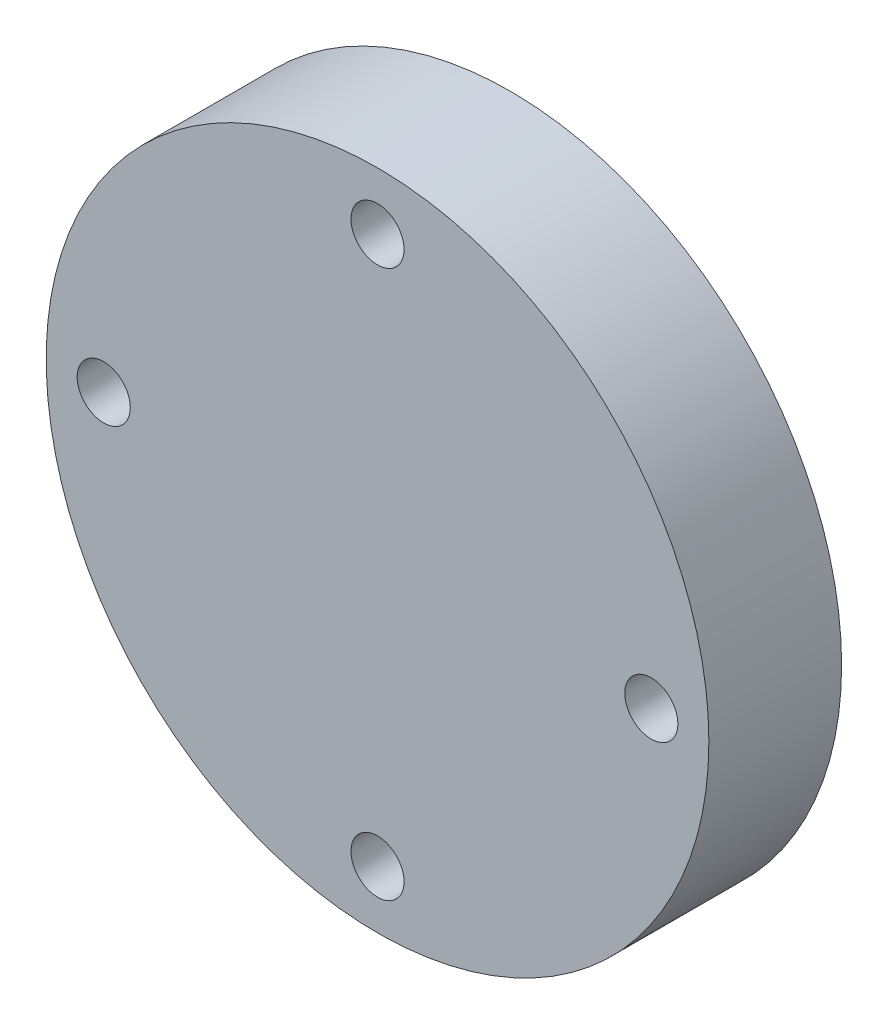
SolidWorks part; units mm, degrees
ref_plane "Front Plane" through (0, 0, 0) normal (0, 0, 1) x (1, 0, 0)
ref_plane "Top Plane" through (0, 0, 0) normal (0, 1, 0) x (1, 0, 0)
ref_plane "Right Plane" through (0, 0, 0) normal (1, 0, 0) x (0, 0, -1)
sketch "Sketch2" plane through (0, 0, 0) normal (0, 0, 1) x (1, 0, 0)
  circle A0 centre (0, 0) radius 19.9686
  circle A5 centre (0, -16.5) radius 1.6
  circle A6 centre (-16.5, 0) radius 1.6
  circle A7 centre (0, 16.5) radius 1.6
  circle A8 centre (16.5, 0) radius 1.6
extrude "Boss-Extrude1" add sketch "Sketch2" along normal blind 8
